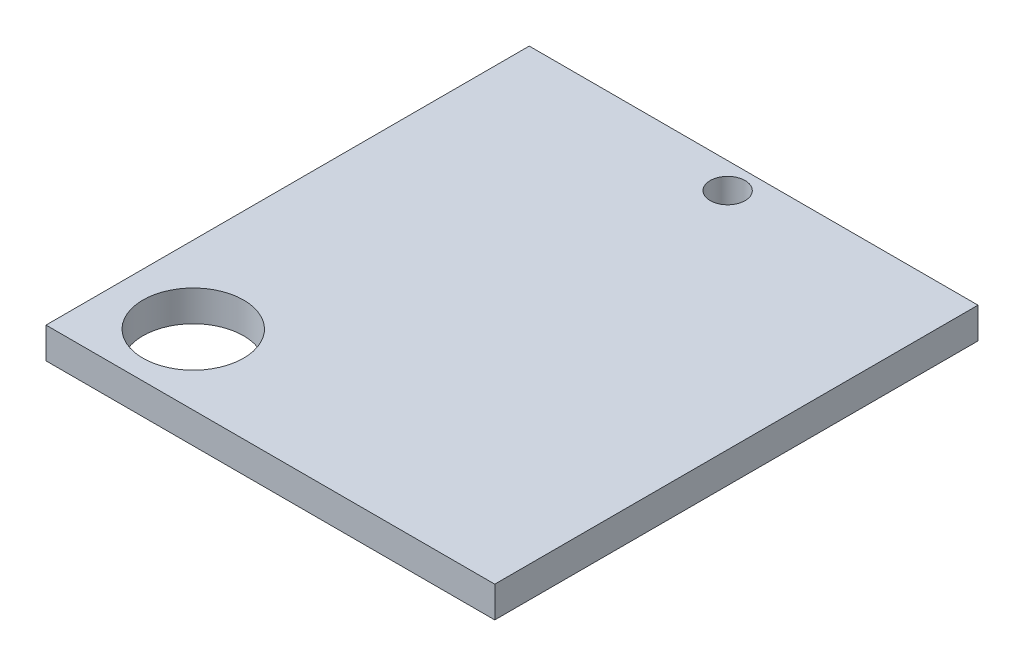
SolidWorks part; units mm, degrees
ref_plane "Plan de face" through (0, 0, 0) normal (0, 0, 1) x (1, 0, 0)
ref_plane "Plan de dessus" through (0, 0, 0) normal (0, 1, 0) x (1, 0, 0)
ref_plane "Plan de droite" through (0, 0, 0) normal (1, 0, 0) x (0, 0, -1)
sketch "Esquisse2" plane through (0, 0, 0) normal (0, 1, 0) x (1, 0, 0)
  line L1 (-28.95, 21.3013) -> (28.95, 21.3013)
  line L2 (-28.95, 21.3013) -> (-28.95, -41.0487)
  line L3 (-28.95, -41.0487) -> (28.95, -41.0487)
  line L4 (28.95, 21.3013) -> (28.95, -41.0487)
  line L5 (-28.95, 21.3013) -> (28.95, -41.0487) construction
  line L6 (-28.95, -41.0487) -> (28.95, 21.3013) construction
  point P0 (0, -9.8737)
  dimension "D1" = 57.9
  dimension "D2" = 62.35
extrude "Boss.-Extru.1" add sketch "Esquisse2" along normal blind 4
sketch "Esquisse3" plane through (0, 0, 0) normal (0, -1, 0) x (1, 0, 0)
  circle A0 centre (-19, 32) radius 6.5
  dimension "D1" = 13
  dimension "D2" = 32
  dimension "D3" = 19
extrude "Enlèv. mat.-Extru.1" cut sketch "Esquisse3" against normal through all
sketch "Esquisse4" plane through (0, 4, 0) normal (0, 1, 0) x (1, 0, 0)
  line L0 (0, 21.3013) -> (0, 17.9513) construction
  line L1 (28.95, 21.3013) -> (-28.95, 21.3013) construction
  circle A0 centre (0, 17.9513) radius 2.25
  point P6 (0, 16.3013)
  point P7 (-0.4575, 16.0944)
  dimension "D2" = 4.5
  dimension "D1" = 3.35
extrude "Enlèv. mat.-Extru.2" cut sketch "Esquisse4" against normal blind 10
